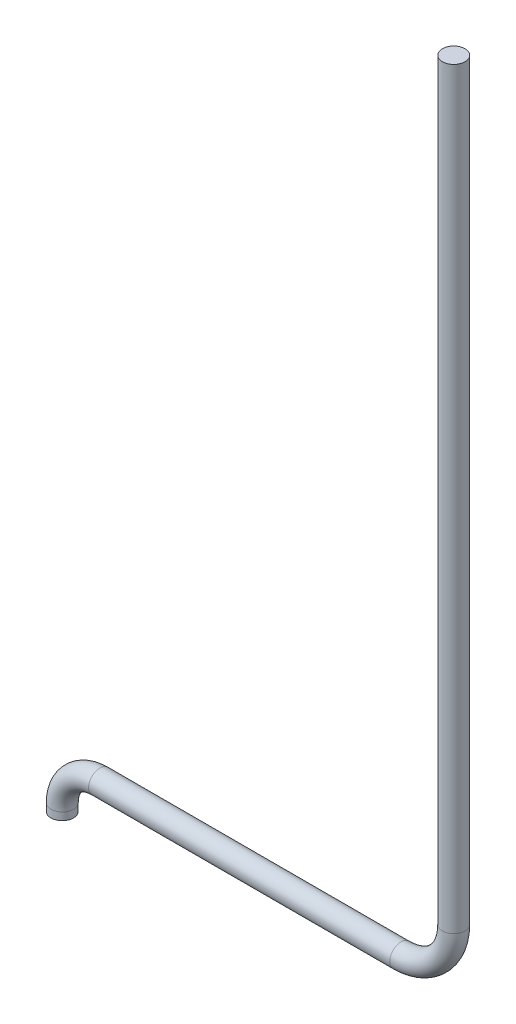
SolidWorks part; units mm, degrees
material "ABS PC"
ref_plane "Front Plane" through (0, 0, 0) normal (0, 0, 1) x (1, 0, 0)
ref_plane "Top Plane" through (0, 0, 0) normal (0, 1, 0) x (1, 0, 0)
ref_plane "Right Plane" through (0, 0, 0) normal (1, 0, 0) x (0, 0, -1)
sketch "Sketch1" plane through (0, 0, 0) normal (0, 0, 1) x (1, 0, 0)
  line L0 (0, 0) -> (0, 10)
  line L1 (50, 60) -> (450, 60)
  line L2 (520, 130) -> (520, 1130)
  arc A0 (0, 10) -> (50, 60) centre (50, 10) cw
  arc A1 (450, 60) -> (520, 130) centre (450, 130) ccw
  dimension "D2" = 50
  dimension "D4" = 70
  dimension "D1" = 10
  dimension "D3" = 400
  dimension "D5" = 1000
sketch "Sketch2" plane through (0, 0, 0) normal (0, 1, 0) x (1, 0, 0)
  circle A0 centre (0, 0) radius 15
  dimension "D1" = 30
sweep "Sweep1" add profiles "Sketch2" path "Sketch1"
shell "Shell1" thickness 5
